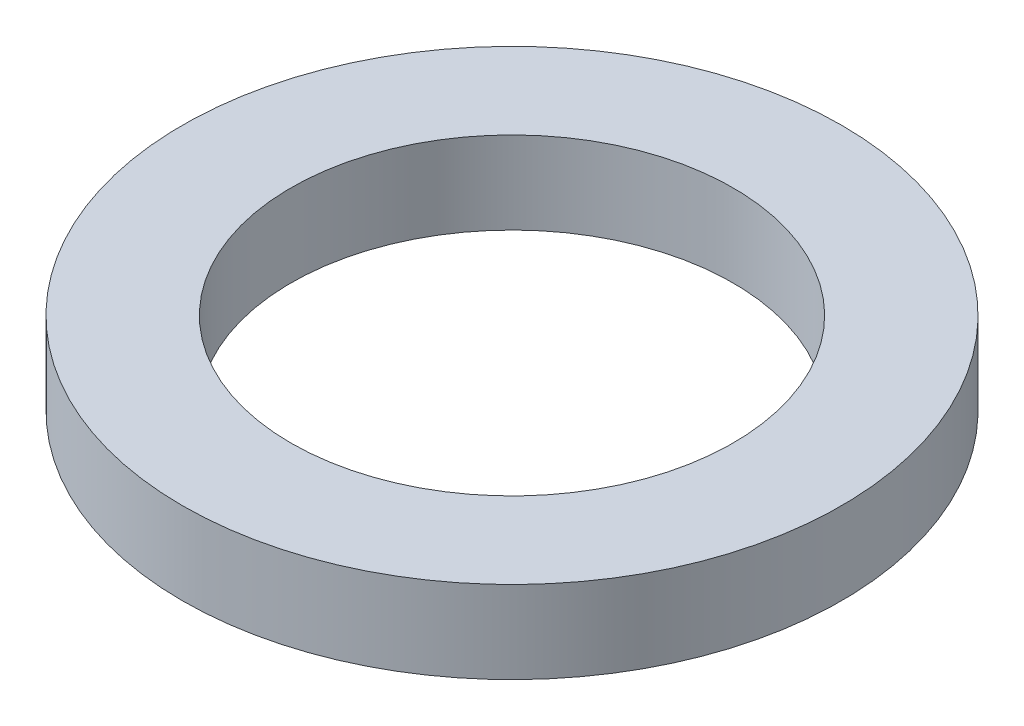
SolidWorks part; units mm, degrees
ref_plane "Спереди" through (0, 0, 0) normal (0, 0, 1) x (1, 0, 0)
ref_plane "Сверху" through (0, 0, 0) normal (0, 1, 0) x (1, 0, 0)
ref_plane "Справа" through (0, 0, 0) normal (1, 0, 0) x (0, 0, -1)
ref_plane "Плоскость4" through (0, 0, 0) normal (0, 0, -1) x (-1, 0, 0)
sketch "Эскиз1" plane through (0, 0, 0) normal (0, 0, -1) x (-1, 0, 0)
  line L0 (-4.025, 1.5) -> (-6, 1.5)
  line L1 (-6, 1.5) -> (-6, 0)
  line L2 (-6, 0) -> (-4.025, 0)
  line L3 (-4.025, 0) -> (-4.025, 1.5)
  line L4 (0, 0) -> (0, 1.9) construction
revolve "Повернуть1" add sketch "Эскиз1" angle 360 about L4
